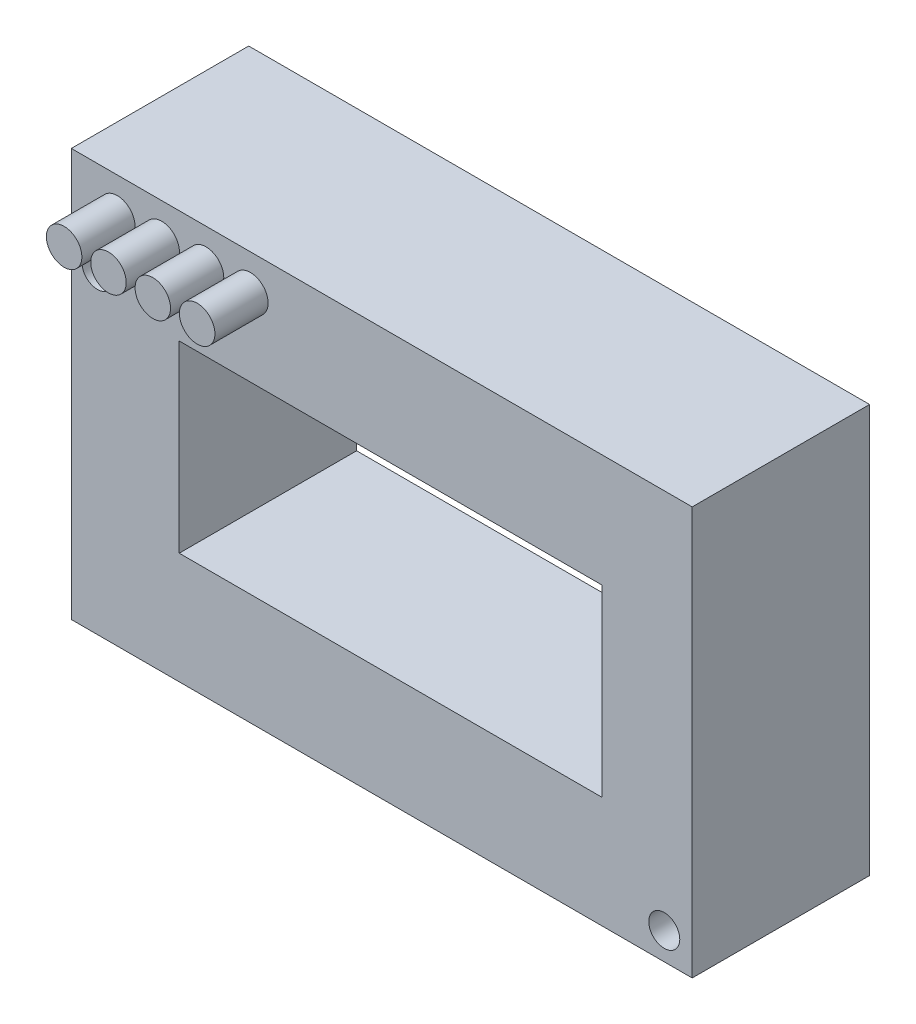
SolidWorks part; units mm, degrees
ref_plane "前基準面" through (0, 0, 0) normal (0, 0, 1) x (1, 0, 0)
ref_plane "上基準面" through (0, 0, 0) normal (0, 1, 0) x (1, 0, 0)
ref_plane "右基準面" through (0, 0, 0) normal (1, 0, 0) x (0, 0, -1)
sketch "草圖1" plane through (0, 0, 0) normal (0, 0, 1) x (1, 0, 0)
  line L1 (-18.141, 8.8263) -> (16.859, 8.8263)
  line L2 (-18.141, 8.8263) -> (-18.141, -14.1737)
  line L3 (-18.141, -14.1737) -> (16.859, -14.1737)
  line L4 (16.859, 8.8263) -> (16.859, -14.1737)
  dimension "D1" = 35
  dimension "D2" = 23
extrude "填料-伸長1" add sketch "草圖1" along normal blind 10
sketch "草圖2" plane through (0, 0, 10) normal (0, 0, 1) x (1, 0, 0)
  line L1 (-12.0581, 2.467) -> (11.7724, 2.467)
  line L2 (-12.0581, 2.467) -> (-12.0581, -7.8941)
  line L3 (-12.0581, -7.8941) -> (11.7724, -7.8941)
  line L4 (11.7724, 2.467) -> (11.7724, -7.8941)
extrude "除料-伸長1" cut sketch "草圖2" against normal blind 10
sketch "草圖3" plane through (0, 0, 10) normal (0, 0, 1) x (1, 0, 0)
  line L0 (16.859, 8.8263) -> (-18.141, 8.8263) construction
  line L1 (-18.141, 8.8263) -> (-18.141, -14.1737) construction
  line L2 (16.859, -14.1737) -> (16.859, 8.8263) construction
  line L3 (-18.141, -14.1737) -> (16.859, -14.1737) construction
  circle A0 centre (-16.666, 3.5513) radius 0.875
  circle A1 centre (15.284, -12.6387) radius 0.875
  dimension "D1" = 1.75
  dimension "D2" = 1.75
  dimension "D4" = 1.475
  dimension "D5" = 1.575
  dimension "D6" = 1.535
  dimension "D3" = 5.275
extrude "除料-伸長2" cut sketch "草圖3" against normal up to next
sketch "草圖4" plane through (0, 0, 10) normal (0, 0, 1) x (1, 0, 0)
  circle A0 centre (-15.5473, 6.8193) radius 1
  circle A1 centre (-13.0473, 6.8193) radius 1
  circle A2 centre (-10.5473, 6.8193) radius 1
  circle A3 centre (-8.0473, 6.8193) radius 1
  dimension "D1" = 2
  dimension "D2" = 2
  dimension "D3" = 2
  dimension "D4" = 2
  dimension "D5" = 2.5
  dimension "D6" = 2.5
  dimension "D7" = 2.5
extrude "填料-伸長2" add sketch "草圖4" along normal blind 3
